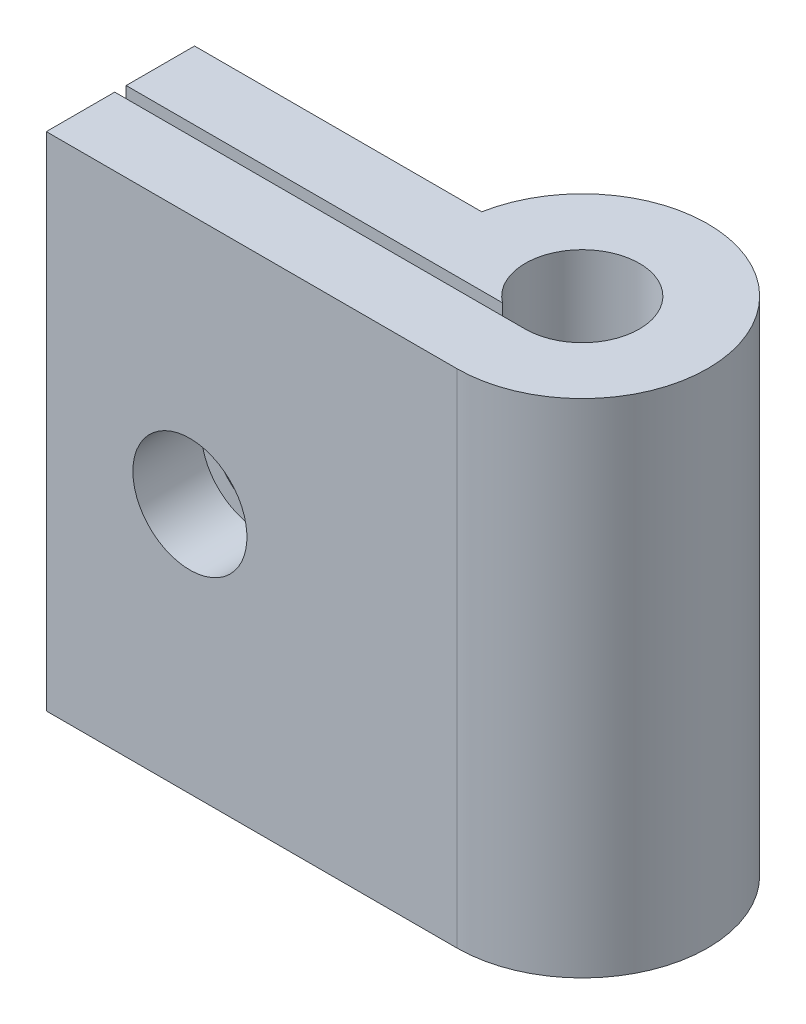
SolidWorks part; units mm, degrees
ref_plane "Alzado" through (0, 0, 0) normal (0, 0, 1) x (1, 0, 0)
ref_plane "Planta" through (0, 0, 0) normal (0, 1, 0) x (1, 0, 0)
ref_plane "Vista lateral" through (0, 0, 0) normal (1, 0, 0) x (0, 0, -1)
sketch "Croquis1" plane through (0, 0, 0) normal (0, 1, 0) x (1, 0, 0)
  line L0 (0, -5.5) -> (-18, -5.5)
  line L1 (-18, -5.5) -> (-18, -2.5)
  line L2 (-18, -2.5) -> (-7.3996, -2.5)
  line L3 (-6.4666, -2) -> (-18, -2)
  line L4 (-18, -2) -> (-18, 1)
  line L5 (-18, 1) -> (-5.4083, 1)
  line L6 (-6.4666, -2) -> (-1.5, -2)
  line L7 (-7.3996, -2.5) -> (0, -2.5)
  arc A0 (0, -2.5) -> (-1.5, -2) centre (0, 0) ccw
  arc A1 (0, -5.5) -> (-5.4083, 1) centre (0, 0) ccw
  dimension "D1" = 2.5
  dimension "D2" = 3
  dimension "D3" = 18
  dimension "D4" = 0.5
extrude "Saliente-Extruir1" add sketch "Croquis1" along normal blind 22
sketch "Croquis2" plane through (0, 0, -1) normal (0, 0, -1) x (-1, 0, 0)
  line L0 (5.4083, 22) -> (18, 0) construction
  circle A0 centre (11.7042, 11) radius 2.5
  dimension "D1" = 5
extrude "Cortar-Extruir1" cut sketch "Croquis2" against normal blind 15
